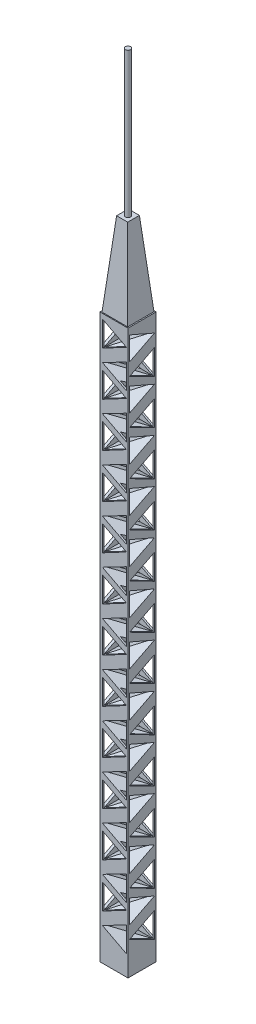
SolidWorks part; units mm, degrees
ref_plane "Alzado" through (0, 0, 0) normal (0, 0, 1) x (1, 0, 0)
ref_plane "Planta" through (0, 0, 0) normal (0, 1, 0) x (1, 0, 0)
ref_plane "Vista lateral" through (0, 0, 0) normal (1, 0, 0) x (0, 0, -1)
sketch "Croquis1" plane through (0, 0, 0) normal (0, 1, 0) x (1, 0, 0)
  line L1 (-200, 200) -> (200, 200)
  line L2 (-200, 200) -> (-200, -200)
  line L3 (-200, -200) -> (200, -200)
  line L4 (200, 200) -> (200, -200)
  line L5 (-200, 200) -> (200, -200) construction
  line L6 (-200, -200) -> (200, 200) construction
  point P0 (0, 0)
  dimension "D1" = 400
  dimension "D2" = 400
extrude "Saliente-Extruir1" add sketch "Croquis1" along normal blind 8000
sketch "Croquis2" plane through (0, 8000, 0) normal (0, 1, 0) x (1, 0, 0)
  line L1 (-182.4346, -187.0692) -> (182.4346, -187.0692)
  line L2 (-182.4346, -187.0692) -> (-182.4346, 187.0692)
  line L3 (-182.4346, 187.0692) -> (182.4346, 187.0692)
  line L4 (182.4346, -187.0692) -> (182.4346, 187.0692)
  line L5 (-182.4346, -187.0692) -> (182.4346, 187.0692) construction
  line L6 (-182.4346, 187.0692) -> (182.4346, -187.0692) construction
  point P0 (0, 0)
extrude "Saliente-Extruir3" add sketch "Croquis2" along normal blind 1186 draft 5 contours L4 L3 L2 L1
sketch "Croquis5" plane through (0, 9186, 0) normal (0, 1, 0) x (1, 0, 0)
  circle A0 centre (0, 0) radius 37.1748
extrude "Saliente-Extruir4" add sketch "Croquis5" along normal blind 2061
sketch "Croquis6" plane through (0, 0, 200) normal (0, 0, 1) x (1, 0, 0)
  line L0 (-163.2789, 7931.1865) -> (-163.2789, 7572.1936)
  line L1 (-163.2789, 7572.1936) -> (178.0225, 7753.3228)
  line L2 (178.0225, 7753.3228) -> (-163.2789, 7931.1865)
  line L3 (178.0225, 7572.1936) -> (178.0225, 7216.7487)
  line L4 (178.0225, 7216.7487) -> (-163.2789, 7394.4711)
  line L5 (-163.2789, 7394.4711) -> (178.0225, 7572.1936)
extrude "Cortar-Extruir1" cut sketch "Croquis6" against normal blind 2061
pattern_linear "MatrizL1" count 12 spacing 630 along (0, -1, 0) of "Cortar-Extruir1"
sketch "Croquis7" plane through (-200, 0, 0) normal (-1, 0, 0) x (0, 0, 1)
  line L0 (-175.5746, 7573.4053) -> (-175.5746, 7216.1755)
  line L1 (-175.5746, 7216.1755) -> (176.5411, 7394.7904)
  line L3 (176.5411, 7394.7904) -> (-175.5746, 7573.4053)
  line L4 (-175.5746, 7751.69) -> (176.5411, 7904.5852)
  line L5 (176.5411, 7904.5852) -> (176.5411, 7573.4053)
  line L6 (176.5411, 7573.4053) -> (-175.5746, 7751.69)
  point P5 (176.5411, 7573.4053)
  point P7 (176.5411, 7904.5852)
extrude "Cortar-Extruir2" cut sketch "Croquis7" against normal blind 2061
pattern_linear "MatrizL2" count 12 spacing 630 along (0, -1, 0) of "Cortar-Extruir2"
